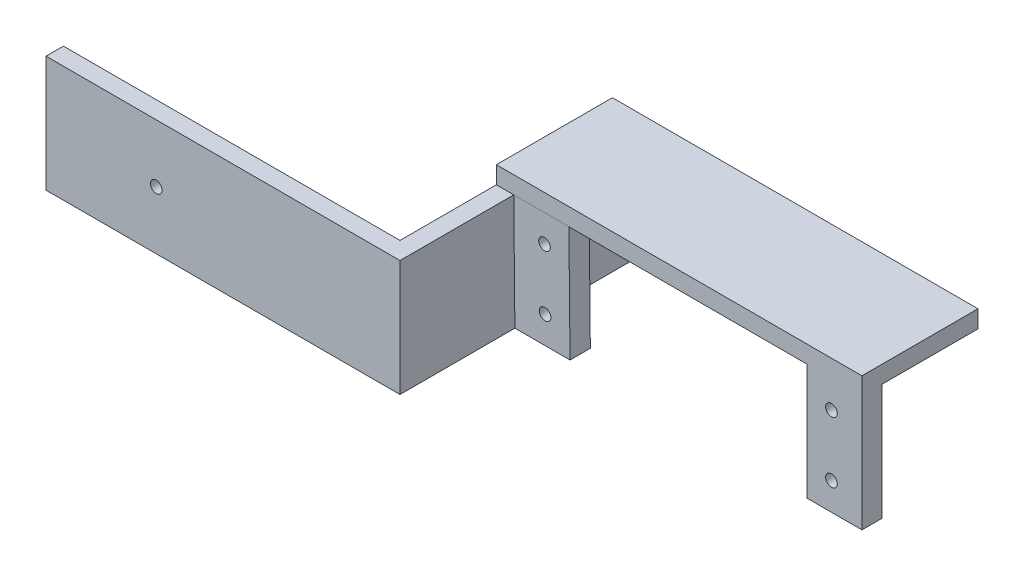
SolidWorks part; units mm, degrees
ref_plane "Alzado" through (0, 0, 0) normal (0, 0, 1) x (1, 0, 0)
ref_plane "Planta" through (0, 0, 0) normal (0, 1, 0) x (1, 0, 0)
ref_plane "Vista lateral" through (0, 0, 0) normal (1, 0, 0) x (0, 0, -1)
sketch "Croquis1" plane through (0, 0, 0) normal (0, 1, 0) x (1, 0, 0)
  line L0 (-63.5286, -28.8157) -> (-2.5286, -28.8157)
  line L1 (-63.5286, -28.8157) -> (-63.5286, -25.8157)
  line L2 (-63.5286, -25.8157) -> (-5.5286, -25.8157)
  line L3 (-2.5286, -28.8157) -> (-2.5286, 10.7843)
  line L4 (-2.5286, 10.7843) -> (-5.5286, 10.7843)
  line L5 (-5.5286, 10.7843) -> (-5.5286, -25.8157)
extrude "Saliente-Extruir1" add sketch "Croquis1" along normal blind 20
sketch "Croquis2" plane through (0, 20, 0) normal (0, 1, 0) x (1, 0, 0)
  line L0 (-2.5286, 10.7843) -> (-5.5286, 10.7843)
  line L1 (-5.5286, 10.7843) -> (-5.5286, -9.2157)
  line L2 (-5.5286, 10.7843) -> (-5.5286, -25.8157) construction
  line L3 (-5.5286, -9.2157) -> (-2.5286, -9.2157)
  line L4 (-2.5286, -28.8157) -> (-2.5286, 10.7843) construction
  line L5 (-2.5286, -9.2157) -> (-2.5286, 10.7843)
extrude "Saliente-Extruir2" add sketch "Croquis2" along normal blind 3
sketch "Croquis3" plane through (-2.5286, 0, 0) normal (1, 0, 0) x (0, 0, -1)
  line L0 (-9.2157, 20) -> (10.7843, 20)
  line L1 (10.7843, 23) -> (10.7843, 0) construction
  line L2 (10.7843, 20) -> (10.7843, 23)
  line L3 (10.7843, 23) -> (-9.2157, 23)
  line L4 (-9.2157, 23) -> (-9.2157, 20)
extrude "Saliente-Extruir3" add sketch "Croquis3" along normal blind 60
sketch "Croquis4" plane through (-2.5286, 0, 0) normal (1, 0, 0) x (0, 0, -1)
  line L0 (-9.2157, 20) -> (-9.0157, 0)
  line L1 (-28.8157, 0) -> (10.7843, 0) construction
  line L2 (-9.0157, 0) -> (-5.5157, 0)
  line L3 (-5.5157, 0) -> (-5.7157, 20)
  line L4 (-9.2157, 20) -> (10.7843, 20) construction
  line L5 (-5.7157, 20) -> (-9.2157, 20)
extrude "Saliente-Extruir4" add sketch "Croquis4" along normal blind 9.5
sketch "Croquis5" plane through (0, 20, 0) normal (0, -1, 0) x (1, 0, 0)
  line L0 (57.4714, 9.2157) -> (57.4714, 5.7157)
  line L1 (57.4714, 9.2157) -> (57.4714, -10.7843) construction
  line L2 (57.4714, 5.7157) -> (47.9714, 5.7157)
  line L3 (47.9714, 5.7157) -> (47.9714, 9.2157)
  line L4 (57.4714, 9.2157) -> (6.9714, 9.2157) construction
  line L5 (47.9714, 9.2157) -> (57.4714, 9.2157)
extrude "Saliente-Extruir6" add sketch "Croquis5" along normal blind 20
sketch "Croquis6" plane through (0, 0, 25.8157) normal (0, 0, -1) x (-1, 0, 0)
  circle A0 centre (44.5286, 10) radius 4
extrude "Cortar-Extruir1" cut sketch "Croquis6" against normal blind 1.2
sketch "Croquis7" plane through (0, 0, 27.0157) normal (0, 0, -1) x (-1, 0, 0)
  circle A0 centre (44.5286, 10) radius 1
extrude "Cortar-Extruir2" cut sketch "Croquis7" against normal blind 1.8
sketch "Croquis8" plane through (0, -0.0901, 9.0148) normal (0, -0.01, 1) x (1, 0, 0)
  circle A0 centre (2.7214, 15.3407) radius 1
  circle A1 centre (2.7214, 4.8402) radius 1
  circle A2 centre (52.2214, 15.3407) radius 1
  circle A3 centre (52.2214, 4.8402) radius 1
extrude "Cortar-Extruir4" cut sketch "Croquis8" against normal mid plane 13.5
